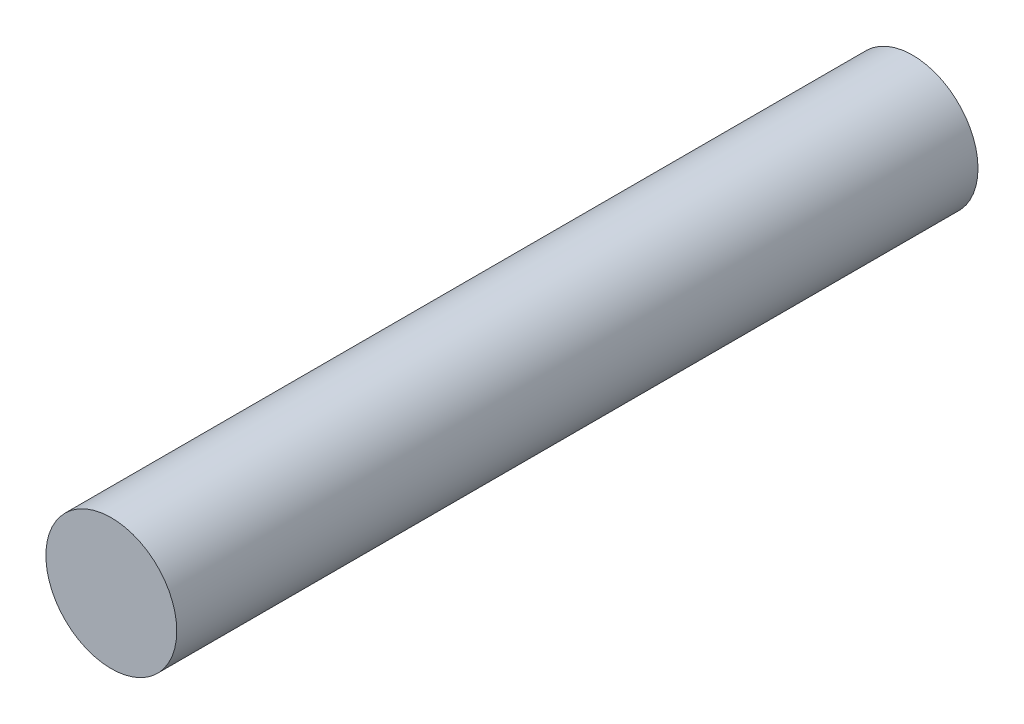
SolidWorks part; units mm, degrees
ref_plane "Front Plane" through (0, 0, 0) normal (0, 0, 1) x (1, 0, 0)
ref_plane "Top Plane" through (0, 0, 0) normal (0, 1, 0) x (1, 0, 0)
ref_plane "Right Plane" through (0, 0, 0) normal (1, 0, 0) x (0, 0, -1)
sketch "Sketch1" plane through (0, 0, 0) normal (0, 0, 1) x (1, 0, 0)
  circle A0 centre (0, 0) radius 2.45
  dimension "D1" = 4.9
extrude "Boss-Extrude1" add sketch "Sketch1" along normal blind 30
